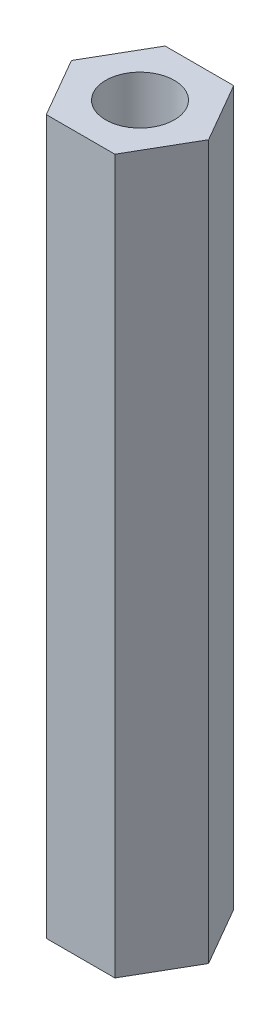
SolidWorks part; units mm, degrees
ref_plane "Front Plane" through (0, 0, 0) normal (0, 0, 1) x (1, 0, 0)
ref_plane "Top Plane" through (0, 0, 0) normal (0, 1, 0) x (1, 0, 0)
ref_plane "Right Plane" through (0, 0, 0) normal (1, 0, 0) x (0, 0, -1)
sketch "Sketch1" plane through (0, 0, 0) normal (0, 1, 0) x (1, 0, 0)
  line L1 (1.25, -2.1651) -> (2.5, 0)
  line L2 (2.5, 0) -> (1.25, 2.1651)
  line L3 (1.25, 2.1651) -> (-1.25, 2.1651)
  line L4 (-1.25, 2.1651) -> (-2.5, 0)
  line L5 (-2.5, 0) -> (-1.25, -2.1651)
  line L6 (-1.25, -2.1651) -> (1.25, -2.1651)
  circle A0 centre (0, 0) radius 2.5 construction
  circle A1 centre (0, 0) radius 1.25
  dimension "D1" = 5
  dimension "D2" = 2.5
extrude "Boss-Extrude1" add sketch "Sketch1" along normal mid plane 26
